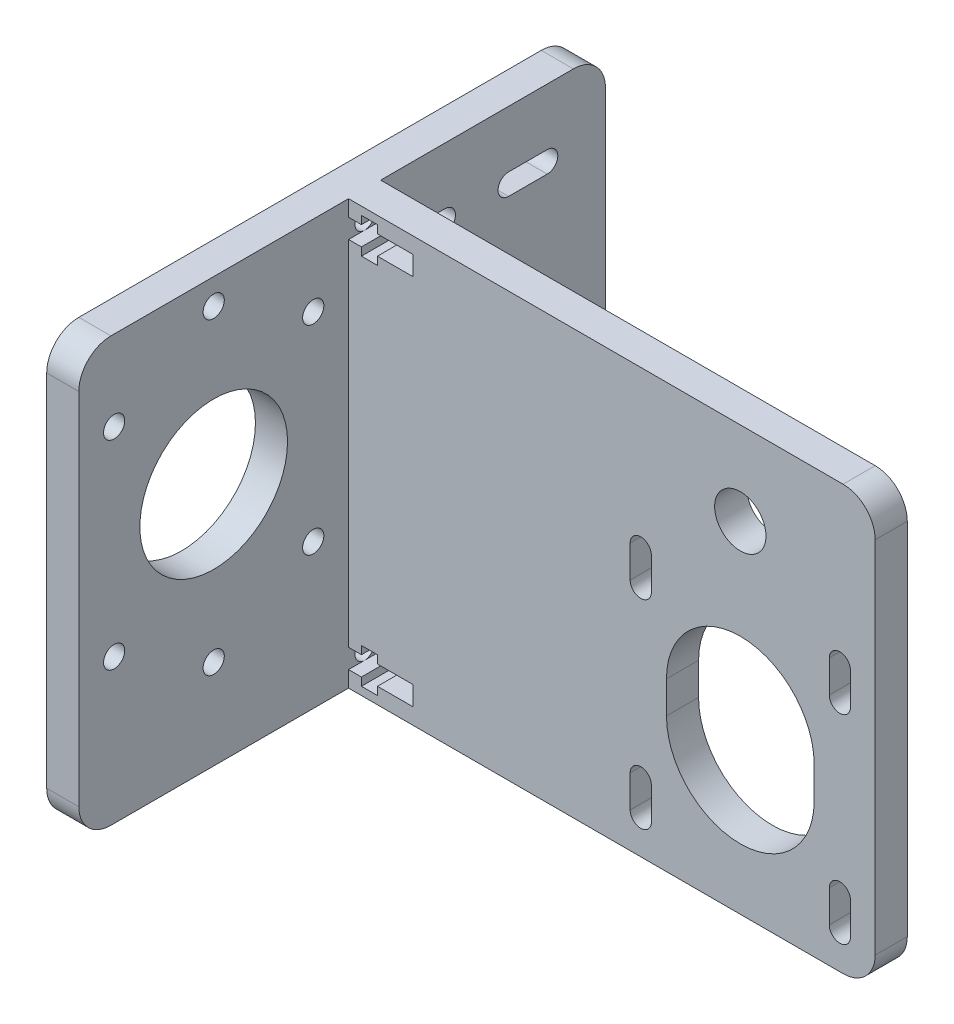
SolidWorks part; units mm, degrees
ref_plane "Front Plane" through (0, 0, 0) normal (0, 0, 1) x (1, 0, 0)
ref_plane "Top Plane" through (0, 0, 0) normal (0, 1, 0) x (1, 0, 0)
ref_plane "Right Plane" through (0, 0, 0) normal (1, 0, 0) x (0, 0, -1)
sketch "Sketch1" plane through (0, 0, 0) normal (0, 1, 0) x (1, 0, 0)
  line L0 (0, 0) -> (0, -42)
  line L1 (0, -42) -> (-5, -42)
  line L2 (-5, -42) -> (-5, 40)
  line L3 (-5, 40) -> (0, 40)
  line L4 (0, 40) -> (0, 5)
  line L5 (0, 5) -> (82, 5)
  line L6 (82, 5) -> (82, 0)
  line L7 (82, 0) -> (0, 0)
  dimension "D1" = 82
  dimension "D2" = 42
  dimension "D3" = 5
  dimension "D4" = 5
  dimension "D5" = 35
extrude "Boss-Extrude1" add sketch "Sketch1" along normal blind 60
sketch "Sketch2" plane through (0, 0, 0) normal (0, 0, 1) x (1, 0, 0)
  line L0 (0, 0) -> (82, 0) construction
  line L1 (45.5, 5.5) -> (76.5, 5.5) construction
  line L2 (45.5, 5.5) -> (45.5, 36.5) construction
  line L3 (45.5, 36.5) -> (76.5, 36.5) construction
  line L4 (76.5, 5.5) -> (76.5, 36.5) construction
  line L5 (45.5, 5.5) -> (76.5, 36.5) construction
  line L6 (45.5, 36.5) -> (76.5, 5.5) construction
  line L8 (82, 60) -> (82, 0) construction
  circle A0 centre (45.5, 36.5) radius 1.65
  circle A1 centre (76.5, 36.5) radius 1.65
  circle A2 centre (76.5, 5.5) radius 1.65
  circle A3 centre (45.5, 5.5) radius 1.65
  circle A4 centre (61, 21) radius 11.5
  point P0 (61, 21)
  dimension "D4" = 3.3
  dimension "D5" = 23
  dimension "D1" = 31
  dimension "D2" = 21
  dimension "D3" = 21
extrude "Cut-Extrude1" cut sketch "Sketch2" against normal blind 60
sketch "Sketch3" plane through (0, 0, 0) normal (1, 0, 0) x (0, 0, -1)
  line L0 (-42, 60) -> (-42, 0) construction
  line L1 (-36.5, 22.5) -> (-5.5, 22.5) construction
  line L2 (-36.5, 22.5) -> (-36.5, 53.5) construction
  line L3 (-36.5, 53.5) -> (-5.5, 53.5) construction
  line L4 (-5.5, 22.5) -> (-5.5, 53.5) construction
  line L5 (-36.5, 22.5) -> (-5.5, 53.5) construction
  line L6 (-36.5, 53.5) -> (-5.5, 22.5) construction
  line L7 (-42, 0) -> (0, 0) construction
  circle A0 centre (-36.5, 53.5) radius 1.65
  circle A1 centre (-5.5, 53.5) radius 1.65
  circle A2 centre (-5.5, 22.5) radius 1.65
  circle A3 centre (-36.5, 22.5) radius 1.65
  circle A4 centre (-21, 38) radius 11.5
  point P0 (-21, 38)
  dimension "D4" = 3.3
  dimension "D5" = 23
  dimension "D1" = 31
  dimension "D2" = 21
  dimension "D3" = 38
extrude "Cut-Extrude2" cut sketch "Sketch3" against normal blind 60
sketch "Sketch4" plane through (0, 0, -5) normal (0, 0, -1) x (-1, 0, 0)
  line L0 (-45.5, 36.5) -> (-45.5, 41.5) construction
  line L1 (-47.15, 36.5) -> (-47.15, 41.5)
  line L2 (-43.85, 36.5) -> (-43.85, 41.5)
  line L3 (-76.5, 36.5) -> (-76.5, 41.5) construction
  line L4 (-78.15, 36.5) -> (-78.15, 41.5)
  line L5 (-74.85, 36.5) -> (-74.85, 41.5)
  line L6 (-76.5, 5.5) -> (-76.5, 10.5) construction
  line L7 (-78.15, 5.5) -> (-78.15, 10.5)
  line L8 (-74.85, 5.5) -> (-74.85, 10.5)
  line L9 (-45.5, 5.5) -> (-45.5, 10.5) construction
  line L10 (-47.15, 5.5) -> (-47.15, 10.5)
  line L11 (-43.85, 5.5) -> (-43.85, 10.5)
  line L12 (-61, 21) -> (-61, 26) construction
  line L13 (-72.5, 21) -> (-72.5, 26)
  line L14 (-49.5, 21) -> (-49.5, 26)
  circle A0 centre (-61, 53) radius 4
  arc A1 (-78.15, 5.5) -> (-74.85, 5.5) centre (-76.5, 5.5) ccw
  arc A2 (-74.85, 10.5) -> (-78.15, 10.5) centre (-76.5, 10.5) ccw
  circle A3 centre (-61, 21) radius 2 construction
  arc A4 (-47.15, 36.5) -> (-43.85, 36.5) centre (-45.5, 36.5) ccw
  arc A5 (-43.85, 41.5) -> (-47.15, 41.5) centre (-45.5, 41.5) ccw
  arc A6 (-78.15, 36.5) -> (-74.85, 36.5) centre (-76.5, 36.5) ccw
  arc A7 (-74.85, 41.5) -> (-78.15, 41.5) centre (-76.5, 41.5) ccw
  arc A8 (-47.15, 5.5) -> (-43.85, 5.5) centre (-45.5, 5.5) ccw
  arc A9 (-43.85, 10.5) -> (-47.15, 10.5) centre (-45.5, 10.5) ccw
  arc A10 (-72.5, 21) -> (-49.5, 21) centre (-61, 21) ccw
  arc A11 (-49.5, 26) -> (-72.5, 26) centre (-61, 26) ccw
  point P8 (-45.5, 39)
  point P15 (-76.5, 39)
  point P22 (-76.5, 8)
  point P29 (-45.5, 8)
  point P34 (-61, 23.5)
  dimension "D1" = 8
  dimension "D2" = 32
  dimension "D3" = 1.65
  dimension "D5" = 11.5
  dimension "D4" = 5
  dimension "D6" = 5
extrude "Cut-Extrude3" cut sketch "Sketch4" against normal blind 21
sketch "Sketch5" plane through (0, 0, 0) normal (1, 0, 0) x (0, 0, -1)
  line L0 (5, 60) -> (40, 60) construction
  line L1 (5, 60) -> (5, 0) construction
  circle A0 centre (19, 38) radius 2.5
  dimension "D1" = 22
  dimension "D2" = 14
  dimension "D3" = 5
extrude "Cut-Extrude4" cut sketch "Sketch5" against normal blind 6
sketch "Sketch7" plane through (-5, 0, 0) normal (-1, 0, 0) x (0, 0, 1)
  line L0 (-7, 55.5) -> (-15, 55.5) construction
  line L1 (-7, 53.85) -> (-15, 53.85)
  line L2 (-7, 57.15) -> (-15, 57.15)
  line L3 (-7, 20.5) -> (-15, 20.5) construction
  line L4 (-7, 18.85) -> (-15, 18.85)
  line L5 (-7, 22.15) -> (-15, 22.15)
  line L6 (-30.9305, 55.5) -> (-24.9305, 55.5) construction
  line L7 (-30.9305, 57.15) -> (-24.9305, 57.15)
  line L8 (-30.9305, 53.85) -> (-24.9305, 53.85)
  line L9 (-30.9305, 20.5) -> (-24.9305, 20.5) construction
  line L10 (-30.9305, 22.15) -> (-24.9305, 22.15)
  line L11 (-30.9305, 18.85) -> (-24.9305, 18.85)
  arc A0 (-7, 53.85) -> (-7, 57.15) centre (-7, 55.5) ccw
  arc A1 (-15, 57.15) -> (-15, 53.85) centre (-15, 55.5) ccw
  arc A2 (-7, 18.85) -> (-7, 22.15) centre (-7, 20.5) ccw
  arc A3 (-15, 22.15) -> (-15, 18.85) centre (-15, 20.5) ccw
  circle A4 centre (21, 38) radius 2 construction
  circle A5 centre (-27.9305, 55.5) radius 1.7128 construction
  circle A6 centre (-27.9305, 20.5) radius 1.65 construction
  arc A7 (-30.9305, 57.15) -> (-30.9305, 53.85) centre (-30.9305, 55.5) ccw
  arc A8 (-24.9305, 53.85) -> (-24.9305, 57.15) centre (-24.9305, 55.5) ccw
  arc A9 (-30.9305, 22.15) -> (-30.9305, 18.85) centre (-30.9305, 20.5) ccw
  arc A10 (-24.9305, 18.85) -> (-24.9305, 22.15) centre (-24.9305, 20.5) ccw
  point P3 (-11, 55.5)
  point P8 (-11, 20.5)
  point P25 (-27.9305, 55.5)
  point P32 (-27.9305, 20.5)
  dimension "D1" = 1.65
  dimension "D2" = 1.65
  dimension "D6" = 1.65
  dimension "D3" = 8
  dimension "D4" = 28
  dimension "D5" = 35
  dimension "D7" = 6
extrude "Cut-Extrude5" cut sketch "Sketch7" against normal blind 10
sketch "Sketch8" plane through (-5, 0, 0) normal (-1, 0, 0) x (0, 0, 1)
  line L44 (-15, 52.35) -> (-7, 52.35)
  line L45 (-7, 58.65) -> (-15, 58.65)
  line L46 (-15, 52.35) -> (-7, 52.35)
  line L47 (-7, 58.65) -> (-15, 58.65)
  line L52 (-7, 23.65) -> (-15, 23.65)
  line L53 (-15, 17.35) -> (-7, 17.35)
  line L54 (-7, 23.65) -> (-15, 23.65)
  line L55 (-15, 17.35) -> (-7, 17.35)
  arc A27 (-15, 58.65) -> (-15, 52.35) centre (-15, 55.5) ccw
  arc A28 (-7, 52.35) -> (-7, 58.65) centre (-7, 55.5) ccw
  arc A29 (-15, 58.65) -> (-15, 52.35) centre (-15, 55.5) ccw
  arc A30 (-7, 52.35) -> (-7, 58.65) centre (-7, 55.5) ccw
  arc A37 (-15, 23.65) -> (-15, 17.35) centre (-15, 20.5) ccw
  arc A38 (-7, 17.35) -> (-7, 23.65) centre (-7, 20.5) ccw
  arc A39 (-15, 23.65) -> (-15, 17.35) centre (-15, 20.5) ccw
  arc A40 (-7, 17.35) -> (-7, 23.65) centre (-7, 20.5) ccw
  dimension "D2" = 1.5
  dimension "D3" = 1.5
sketch "Sketch9" plane through (0, 0, 0) normal (1, 0, 0) x (0, 0, -1)
  circle A0 centre (19, 38) radius 5.25
  dimension "D1" = 10.5
extrude "Cut-Extrude7" cut sketch "Sketch9" against normal blind 3
chamfer "Chamfer1" distance 1 angle 45 1 edges at (-3, 38, -21.5)
sketch "Sketch10" plane through (0, 60, 0) normal (0, 1, 0) x (1, 0, 0)
  line L1 (-5, 40) -> (0, 40)
  line L2 (-5, 40) -> (-5, -42)
  line L3 (-5, -42) -> (0, -42)
  line L4 (0, 40) -> (0, -42)
extrude "Boss-Extrude2" add sketch "Sketch10" along normal blind 6
fillet "Fillet1" radius 5 5 edges at (82, 0, -2.5) (-2.5, 66, -40) (-2.5, 66, 42) (-2.5, 0, 42) (-2.5, 0, -40)
sketch "Sketch11" plane through (-5, 0, 0) normal (-1, 0, 0) x (0, 0, 1)
  circle A0 centre (21, 62) radius 1.65
  circle A1 centre (21, 14) radius 1.65
  circle A2 centre (21, 38) radius 2 construction
  circle A3 centre (21, 38) radius 2.5 construction
  point P4 (0, 0)
  point P6 (0, 0)
  dimension "D1" = 24
  dimension "D2" = 24
  dimension "D3" = 3.3
extrude "Cut-Extrude8" cut sketch "Sketch11" against normal blind 10
sketch "Sketch12" plane through (-5, 0, 0) normal (-1, 0, 0) x (0, 0, 1)
  line L0 (-15, 38) -> (-7, 38) construction
  line L1 (-15, 41.5) -> (-7, 41.5)
  line L2 (-15, 34.5) -> (-7, 34.5)
  arc A0 (-15, 41.5) -> (-15, 34.5) centre (-15, 38) ccw
  arc A1 (-7, 34.5) -> (-7, 41.5) centre (-7, 38) ccw
  point P3 (-11, 38)
  point P8 (-12.6272, 34.5)
  point P9 (0, 0)
  dimension "D1" = 3.5
  dimension "D2" = 8
extrude "Cut-Extrude9" cut sketch "Sketch12" against normal blind 5
sketch "Sketch13" plane through (0, 60, 0) normal (0, 1, 0) x (1, 0, 0)
  line L1 (0, 0) -> (82, 0)
  line L2 (0, 0) -> (0, 5)
  line L3 (0, 5) -> (82, 5)
  line L4 (82, 0) -> (82, 5)
extrude "Boss-Extrude3" add sketch "Sketch13" along normal blind 6
fillet "Fillet2" radius 5 1 edges at (82, 66, -2.5)
sketch "Sketch14" plane through (-5, 0, 0) normal (-1, 0, 0) x (0, 0, 1)
  line L0 (-40, 61) -> (-40, 5) construction
  line L1 (-35, 66) -> (37, 66) construction
  line L2 (-35, 0) -> (37, 0) construction
  circle A0 centre (-2.5, 62) radius 1.5
  circle A1 centre (-2.5, 4) radius 1.5
  point P12 (0, 0)
  dimension "D1" = 3
  dimension "D2" = 37.5
  dimension "D3" = 4
  dimension "D4" = 3
  dimension "D5" = 4
extrude "Cut-Extrude10" cut sketch "Sketch14" against normal blind 5
sketch "Sketch15" plane through (0, 0, 0) normal (0, 0, 1) x (1, 0, 0)
  line L1 (0, 63.5) -> (2, 63.5)
  line L2 (0, 63.5) -> (0, 60.5)
  line L3 (0, 60.5) -> (2, 60.5)
  line L4 (10, 63.5) -> (10, 60.5)
  line L5 (0, 66) -> (77, 66) construction
  line L6 (0, 61) -> (0, 66) construction
  line L7 (-5, 66) -> (-5, 61) construction
  line L8 (2, 64.75) -> (4.5, 64.75)
  line L9 (2, 64.75) -> (2, 63.5)
  line L10 (2, 59.25) -> (4.5, 59.25)
  line L11 (4.5, 64.75) -> (4.5, 63.5)
  line L12 (4.5, 60.5) -> (4.5, 59.25)
  line L13 (4.5, 60.5) -> (10, 60.5)
  line L14 (2, 60.5) -> (2, 59.25)
  line L15 (4.5, 63.5) -> (10, 63.5)
  line L16 (82, 33) -> (-49.9208, 33) construction
  line L17 (82, 61) -> (82, 5) construction
  line L18 (4.5, 2.5) -> (10, 2.5)
  line L19 (2, 5.5) -> (2, 6.75)
  line L20 (4.5, 5.5) -> (10, 5.5)
  line L21 (4.5, 5.5) -> (4.5, 6.75)
  line L22 (4.5, 1.25) -> (4.5, 2.5)
  line L23 (2, 6.75) -> (4.5, 6.75)
  line L24 (2, 1.25) -> (2, 2.5)
  line L25 (2, 1.25) -> (4.5, 1.25)
  line L26 (10, 2.5) -> (10, 5.5)
  line L27 (0, 5.5) -> (2, 5.5)
  line L28 (0, 2.5) -> (0, 5.5)
  line L29 (0, 2.5) -> (2, 2.5)
  dimension "D1" = 2.5
  dimension "D2" = 10
  dimension "D3" = 3
  dimension "D4" = 2.5
  dimension "D5" = 7
  dimension "D6" = 5.5
  dimension "D7" = 1.25
extrude "Cut-Extrude11" cut sketch "Sketch15" against normal blind 5
